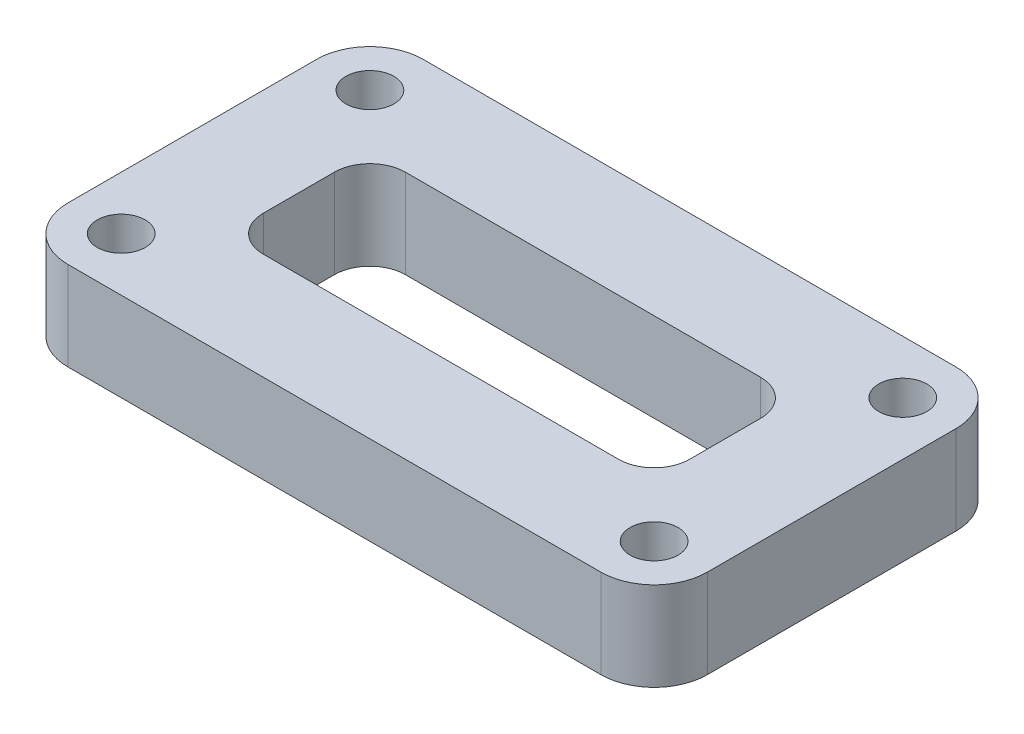
SolidWorks part; units mm, degrees
material "POM"
ref_plane "前视基准面" through (0, 0, 0) normal (0, 0, 1) x (1, 0, 0)
ref_plane "上视基准面" through (0, 0, 0) normal (0, 1, 0) x (1, 0, 0)
ref_plane "右视基准面" through (0, 0, 0) normal (1, 0, 0) x (0, 0, -1)
sketch "草图1" plane through (0, 0, 0) normal (0, 1, 0) x (1, 0, 0)
  line L0 (18, 20) -> (18, 0) construction
  line L1 (0, 0) -> (36, 0)
  line L2 (0, 0) -> (0, 20)
  line L3 (0, 20) -> (36, 20)
  line L4 (36, 0) -> (36, 20)
  line L5 (0, 10) -> (36, 10) construction
  line L6 (6, 6) -> (6, 14)
  line L7 (6, 14) -> (30, 14)
  line L8 (30, 6) -> (30, 14)
  line L9 (6, 6) -> (30, 6)
  circle A0 centre (3, 17) radius 1.35
  circle A1 centre (33, 17) radius 1.35
  circle A2 centre (33, 3) radius 1.35
  circle A3 centre (3, 3) radius 1.35
  dimension "D3" = 2.7
  dimension "D4" = 14
  dimension "D5" = 30
  dimension "D1" = 36
  dimension "D2" = 20
  dimension "D6" = 6
extrude "凸台-拉伸1" add sketch "草图1" along normal blind 5
fillet "圆角1" radius 3 4 edges at (0, 2.5, -20) (36, 2.5, -20) (36, 2.5, 0) (0, 2.5, 0)
fillet "圆角2" radius 2 4 edges at (30, 2.5, -6) (30, 2.5, -14) (6, 2.5, -6) (6, 2.5, -14)
